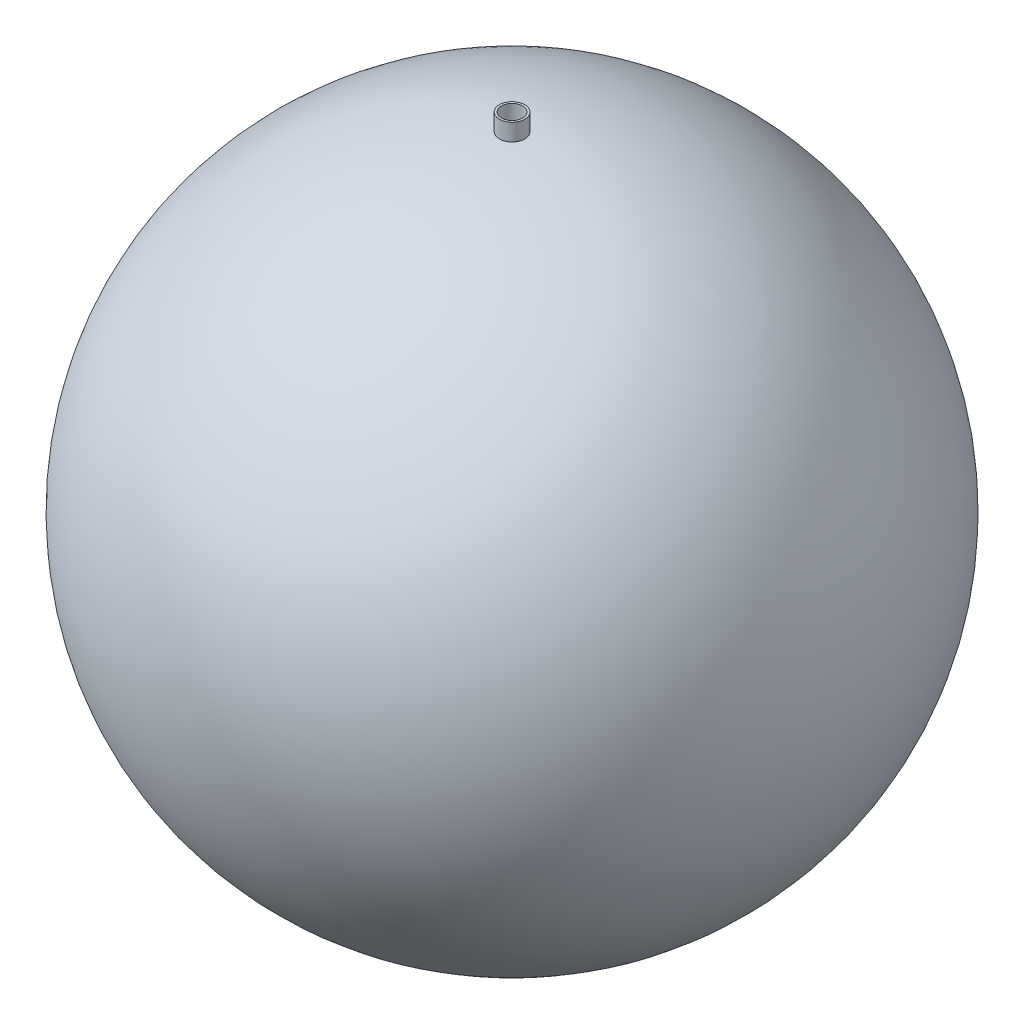
SolidWorks part; units mm, degrees
material "Titanium"
ref_plane "Front Plane" through (0, 0, 0) normal (0, 0, 1) x (1, 0, 0)
ref_plane "Top Plane" through (0, 0, 0) normal (0, 1, 0) x (1, 0, 0)
ref_plane "Right Plane" through (0, 0, 0) normal (1, 0, 0) x (0, 0, -1)
sketch "Sketch74" plane through (0, 0, 0) normal (0, 0, 1) x (1, 0, 0)
  line L0 (0, 0) -> (0, 965.7764) construction
  line L1 (0, 965.7764) -> (0, 0) construction
  line L2 (0, 0) -> (0, -1000.7025) construction
  line L3 (0, 781.5925) -> (0, 771.5925)
  line L4 (0, -771.5925) -> (0, -781.5925)
  arc A0 (0, -781.5925) -> (0, 781.5925) centre (0, 0) ccw
  arc A2 (0, -771.5925) -> (0, 771.5925) centre (0, 0) ccw
  dimension "D1" = 1563.185
  dimension "D2" = 1543.185
revolve "Revolve4" add sketch "Sketch74" angle 360 about L0
ref_plane "Plane1" through (0, 771.5925, 0) normal (0, 1, 0) x (1, 0, 0)
sketch "Sketch76" plane through (0, 771.5925, 0) normal (0, 1, 0) x (1, 0, 0)
  circle A0 centre (0, 0) radius 30
  dimension "D1" = 60
extrude "Boss-Extrude1" add sketch "Sketch76" along normal blind 50
sketch "Sketch78" plane through (0, 0, 0) normal (0, 1, 0) x (1, 0, 0)
  circle A0 centre (0, 0) radius 25
  dimension "D1" = 50
extrude "Cut-Extrude1" cut sketch "Sketch78" along normal through all
